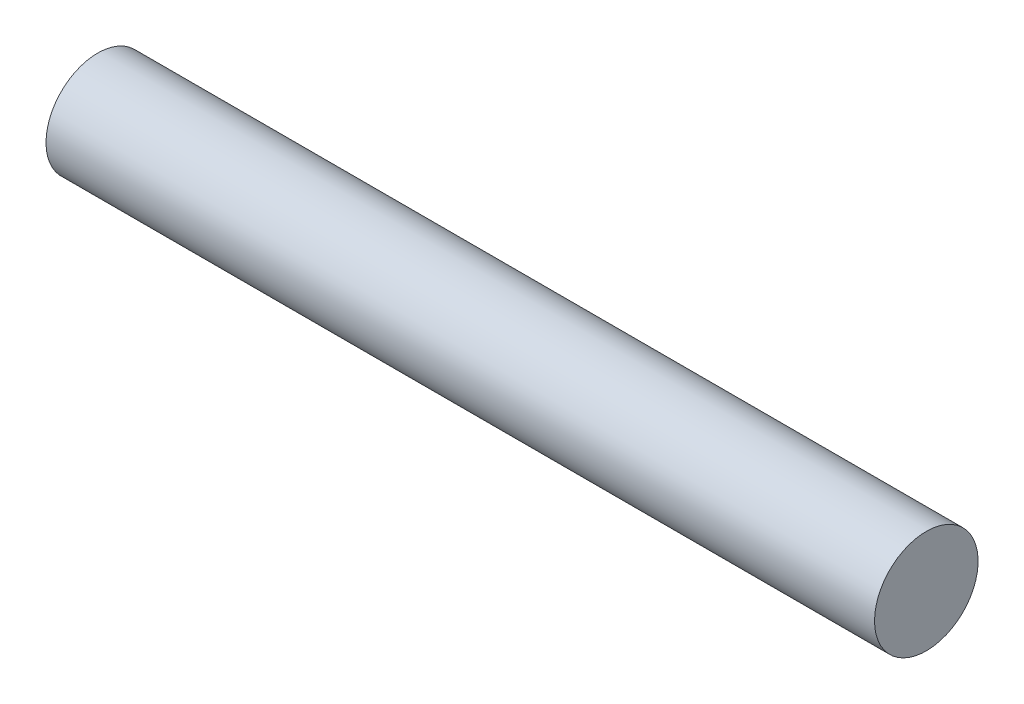
SolidWorks part; units mm, degrees
ref_plane "Front Plane" through (0, 0, 0) normal (0, 0, 1) x (1, 0, 0)
ref_plane "Top Plane" through (0, 0, 0) normal (0, 1, 0) x (1, 0, 0)
ref_plane "Right Plane" through (0, 0, 0) normal (1, 0, 0) x (0, 0, -1)
sketch "Sketch1" plane through (0, 0, 0) normal (1, 0, 0) x (0, 0, -1)
  circle A0 centre (0, 0) radius 1.1906
  dimension "D1" = 2.3813
extrude "Boss-Extrude1" add sketch "Sketch1" along normal blind 19.05
